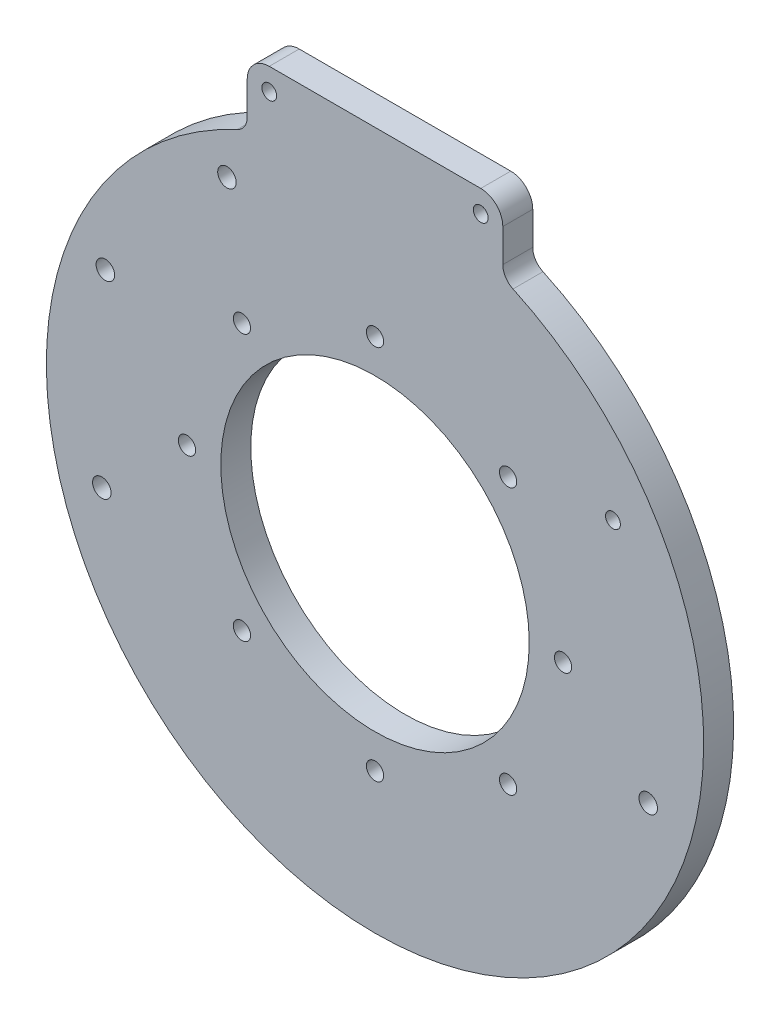
SolidWorks part; units mm, degrees
ref_plane "Front Plane" through (0, 0, 0) normal (0, 0, 1) x (1, 0, 0)
ref_plane "Top Plane" through (0, 0, 0) normal (0, 1, 0) x (1, 0, 0)
ref_plane "Right Plane" through (0, 0, 0) normal (1, 0, 0) x (0, 0, -1)
sketch "Sketch1" plane through (0, 0, 0) normal (0, 0, 1) x (1, 0, 0)
  line L0 (-60, 209.5) -> (60, 209.5)
  line L1 (-72.5, 197) -> (-72.5, 178.3043)
  line L2 (72.5, 197) -> (72.5, 178.3043)
  circle A0 centre (-84, 143) radius 4.5
  circle A1 centre (-60, 197) radius 4
  circle A2 centre (60, 197) radius 3.5
  circle A3 centre (135, 84) radius 3.5
  circle A4 centre (155, -45) radius 4.5
  circle A6 centre (-155, -45) radius 4.5
  circle A7 centre (0, 0) radius 87.5
  circle A8 centre (-153, 63) radius 4.5
  arc A9 (-78.3008, 169.2287) -> (78.3008, 169.2287) centre (0, 0) ccw
  arc A10 (-60, 209.5) -> (-72.5, 197) centre (-60, 197) ccw
  arc A11 (72.5, 197) -> (60, 209.5) centre (60, 197) ccw
  arc A12 (72.5, 178.3043) -> (78.3008, 169.2287) centre (82.5, 178.3043) ccw
  arc A13 (-72.5, 178.3043) -> (-78.3008, 169.2287) centre (-82.5, 178.3043) cw
  dimension "D9" = 155
  dimension "D10" = 7
  dimension "D11" = 175
  dimension "D17" = 9
  dimension "D18" = 25
  dimension "D19" = 10
  dimension "D1" = 197
  dimension "D2" = 60
  dimension "D3" = 60
  dimension "D4" = 197
  dimension "D5" = 84
  dimension "D6" = 143
  dimension "D7" = 84
  dimension "D8" = 135
  dimension "D12" = 45
  dimension "D13" = 155
  dimension "D14" = 45
  dimension "D15" = 153
  dimension "D16" = 63
extrude "Boss-Extrude1" add sketch "Sketch1" along normal blind 17
sketch "Sketch2" plane through (0, 0, 17) normal (0, 0, 1) x (1, 0, 0)
  line L0 (0, 106.68) -> (0, 0) construction
  line L1 (0, 0) -> (75.5072, 75.5072) construction
  circle A0 centre (0, 0) radius 106.68 construction
  circle A1 centre (75.5072, 75.5072) radius 2.5
  circle A2 centre (75.5072, -75.5072) radius 2.5
  circle A3 centre (-75.5072, -75.5072) radius 2.5
  circle A4 centre (-75.5072, 75.5072) radius 2.5
  circle A5 centre (0, 106.68) radius 2.5
  circle A6 centre (106.68, 0) radius 2.5
  circle A7 centre (0, -106.68) radius 2.5
  circle A8 centre (-106.68, 0) radius 2.5
  point P13 (0, 0)
  point P22 (0, 0)
  dimension "D1" = 213.36
  dimension "D3" = 5
  dimension "D2" = 45
  dimension "D4" = 4
  dimension "D5" = 4
hole_wizard "3/8 Clearance Hole1" positions "3DSketch1" profile "Sketch3" hole size "3/8" standard "ANSI Inch"
sketch3d "3DSketch1"
  point P0 (75.5072, 75.5072, 17)
  point P3 (75.5072, -75.5072, 17)
  point P6 (-75.5072, -75.5072, 17)
  point P9 (-75.5072, 75.5072, 17)
  point P13 (0, 106.68, 17)
  point P16 (106.68, 0, 17)
  point P19 (-106.68, 0, 17)
  point P22 (0, -106.68, 17)
sketch "Sketch3" plane through (75.5072, 75.5072, 17) normal (1, 0, 0) x (0, -1, 0)
  line L0 (0, 0) -> (0, 54.2055)
  line L1 (0, 54.2055) -> (4.9022, 51.26)
  line L2 (4.9022, 51.26) -> (4.9022, 0)
  line L5 (4.9022, 0) -> (0, 0)
  line L10 (0, 54.2055) -> (-4.9022, 51.26) construction
  line L11 (0, -6.35) -> (0, 107.95) construction
  dimension "Hole Dia." = 9.8044
  dimension "Hole Depth" = 51.26
  dimension "Drill Angle" = 118
hole_wizard "M10 Clearance Hole1" positions "3DSketch2" profile "Sketch4" hole size "M10" standard "ANSI Metric"
sketch3d "3DSketch2"
  line L0 (155, -45, 17) -> (155, -45, 0) construction
  line L1 (-155, -45, 17) -> (-155, -45, 0) construction
  line L2 (-153, 63, 17) -> (-153, 63, 0) construction
  line L3 (-84, 143, 17) -> (-84, 143, 0) construction
  point P0 (155, -45, 17)
  point P4 (-155, -45, 17)
  point P8 (-153, 63, 17)
  point P12 (-84, 143, 17)
sketch "Sketch4" plane through (155, -45, 17) normal (1, 0, 0) x (0, -1, 0)
  line L0 (0, 0) -> (0, 54.4145)
  line L1 (0, 54.4145) -> (5.25, 51.26)
  line L2 (5.25, 51.26) -> (5.25, 0)
  line L5 (5.25, 0) -> (0, 0)
  line L10 (0, 54.4145) -> (-5.25, 51.26) construction
  line L11 (0, -6.35) -> (0, 107.95) construction
  dimension "Hole Dia." = 10.5
  dimension "Hole Depth" = 51.26
  dimension "Drill Angle" = 118
hole_wizard "M8 Clearance Hole1" positions "3DSketch3" profile "Sketch5" hole size "M8" standard "ANSI Metric"
sketch3d "3DSketch3"
  line L0 (-60, 197, 17) -> (-60, 197, 0) construction
  line L1 (60, 197, 17) -> (60, 197, 0) construction
  line L2 (135, 84, 17) -> (135, 84, 0) construction
  point P0 (-60, 197, 17)
  point P4 (60, 197, 17)
  point P8 (135, 84, 17)
sketch "Sketch5" plane through (-60, 197, 17) normal (1, 0, 0) x (0, -1, 0)
  line L0 (0, 0) -> (0, 53.7836)
  line L1 (0, 53.7836) -> (4.2, 51.26)
  line L2 (4.2, 51.26) -> (4.2, 0)
  line L5 (4.2, 0) -> (0, 0)
  line L10 (0, 53.7836) -> (-4.2, 51.26) construction
  line L11 (0, -6.35) -> (0, 107.95) construction
  dimension "Hole Dia." = 8.4
  dimension "Hole Depth" = 51.26
  dimension "Drill Angle" = 118
